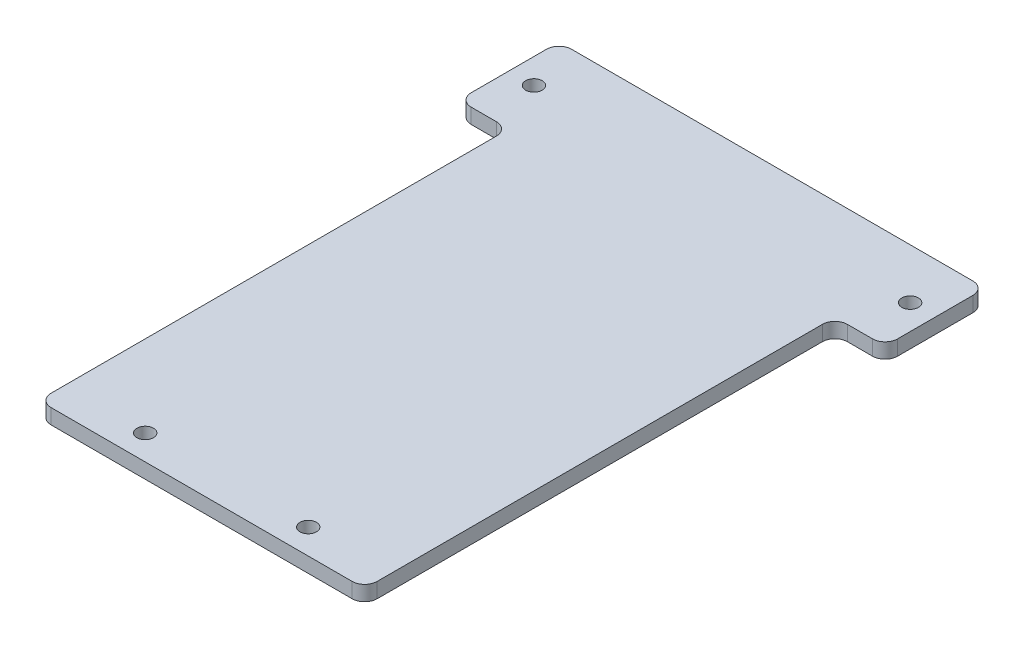
SolidWorks part; units mm, degrees
material "Acrylic (Medium-high impact)"
ref_plane "Front Plane" through (0, 0, 0) normal (0, 0, 1) x (1, 0, 0)
ref_plane "Top Plane" through (0, 0, 0) normal (0, 1, 0) x (1, 0, 0)
ref_plane "Right Plane" through (0, 0, 0) normal (1, 0, 0) x (0, 0, -1)
sketch "Sketch1" plane through (0, 0, 0) normal (0, 1, 0) x (1, 0, 0)
  line L0 (-85, 93.75) -> (-65, 93.75)
  line L1 (-65, -93.75) -> (65, -93.75)
  line L2 (-65, -93.75) -> (-65, 93.75)
  line L3 (-65, 93.75) -> (65, 93.75) construction
  line L4 (65, -93.75) -> (65, 93.75)
  line L5 (-65, -93.75) -> (65, 93.75) construction
  line L6 (-65, 93.75) -> (65, -93.75) construction
  line L7 (-85, 133.75) -> (85, 133.75)
  line L8 (-85, 133.75) -> (-85, 93.75)
  line L9 (-85, 93.75) -> (85, 93.75) construction
  line L10 (85, 133.75) -> (85, 93.75)
  line L11 (-85, 133.75) -> (85, 93.75) construction
  line L12 (-85, 93.75) -> (85, 133.75) construction
  line L13 (65, 93.75) -> (85, 93.75)
  point P0 (0, 0)
  point P6 (0, 113.75)
  dimension "D1" = 187.5
  dimension "D2" = 130
  dimension "D3" = 170
  dimension "D4" = 40
extrude "Boss-Extrude2" add sketch "Sketch1" along normal blind 6
sketch "Sketch3" plane through (0, 6, 0) normal (0, 1, 0) x (1, 0, 0)
  line L0 (-32.5, -93.75) -> (-32.5, -73.75) construction
  line L5 (-65, -93.75) -> (65, -93.75) construction
  line L6 (-85, 133.75) -> (-65, 133.75) construction
  line L7 (-85, 133.75) -> (-85, 93.75) construction
  line L8 (-85, 93.75) -> (-65, 93.75) construction
  line L9 (-65, 133.75) -> (-65, 93.75) construction
  line L14 (0, -93.75) -> (-65, -93.75) construction
  line L15 (0, -93.75) -> (0, -73.75) construction
  line L16 (0, -73.75) -> (-65, -73.75) construction
  line L17 (-65, -93.75) -> (-65, -73.75) construction
  line L18 (-65, 93.75) -> (-65, -93.75) construction
  line L19 (-85, 113.75) -> (-65, 113.75) construction
  circle A0 centre (-75, 113.75) radius 3.3
  circle A2 centre (-32.5, -83.75) radius 3.3
  circle A4 centre (75, 113.75) radius 3.3
  circle A5 centre (32.5, -83.75) radius 3.3
  point P19 (0, 0)
  dimension "D3" = 6.6
  dimension "D1" = 20
extrude "Cut-Extrude1" cut sketch "Sketch3" against normal through all
fillet "Fillet1" radius 5 8 edges at (-65, 3, -93.75) (-85, 3, -133.75) (-85, 3, -93.75) (85, 3, -133.75) (85, 3, -93.75) (65, 3, -93.75) (65, 3, 93.75) (-65, 3, 93.75)
